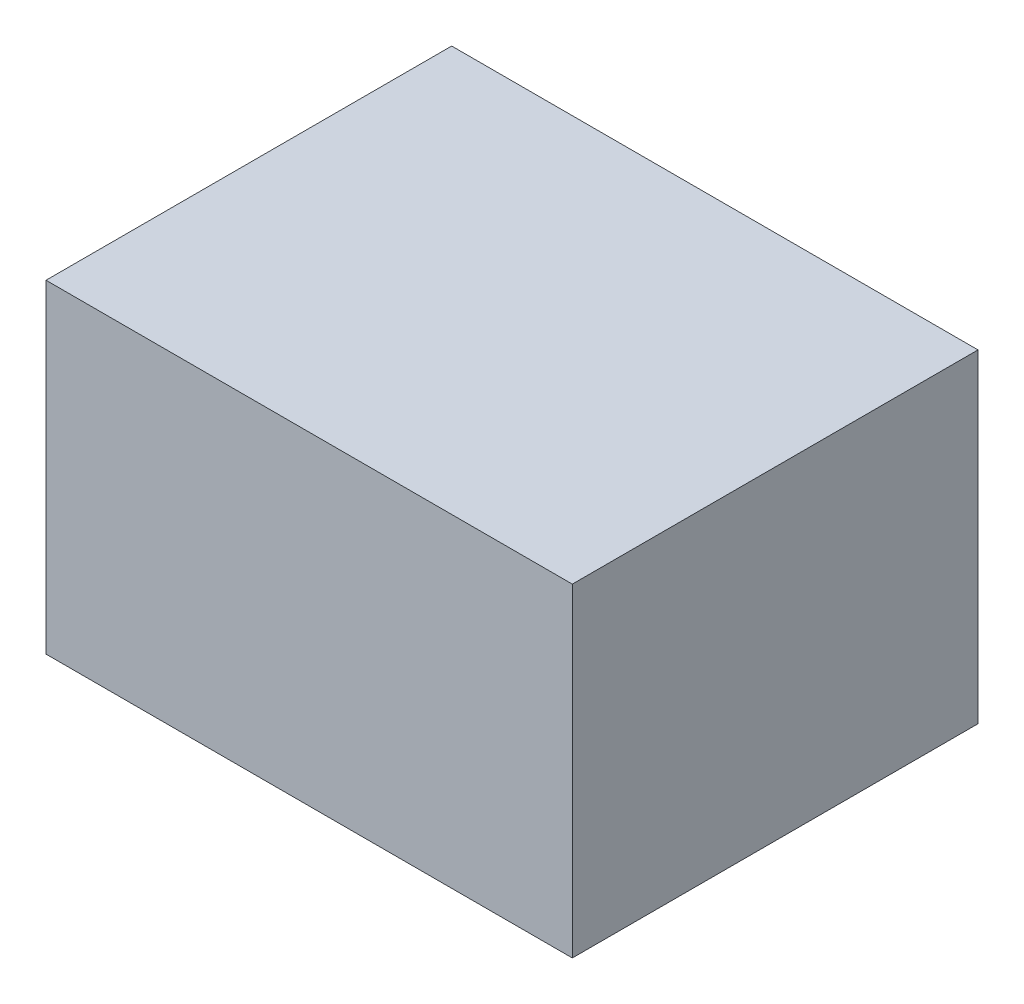
SolidWorks part; units mm, degrees
ref_plane "前视基准面" through (0, 0, 0) normal (0, 0, 1) x (1, 0, 0)
ref_plane "上视基准面" through (0, 0, 0) normal (0, 1, 0) x (1, 0, 0)
ref_plane "右视基准面" through (0, 0, 0) normal (1, 0, 0) x (0, 0, -1)
sketch "草图1" plane through (0, 0, 0) normal (0, 1, 0) x (1, 0, 0)
  line L1 (-42.2637, -32.5757) -> (42.2637, -32.5757)
  line L2 (-42.2637, -32.5757) -> (-42.2637, 32.5757)
  line L3 (-42.2637, 32.5757) -> (42.2637, 32.5757)
  line L4 (42.2637, -32.5757) -> (42.2637, 32.5757)
  line L5 (-42.2637, -32.5757) -> (42.2637, 32.5757) construction
  line L6 (-42.2637, 32.5757) -> (42.2637, -32.5757) construction
  point P0 (0, 0)
extrude "凸台-拉伸1" add sketch "草图1" along normal blind 52
sketch "草图2" plane through (0, 52, 0) normal (0, 1, 0) x (1, 0, 0)
  line L0 (42.2637, -32.5757) -> (42.2637, 32.5757) construction
  point P0 (42.2637, 0)
